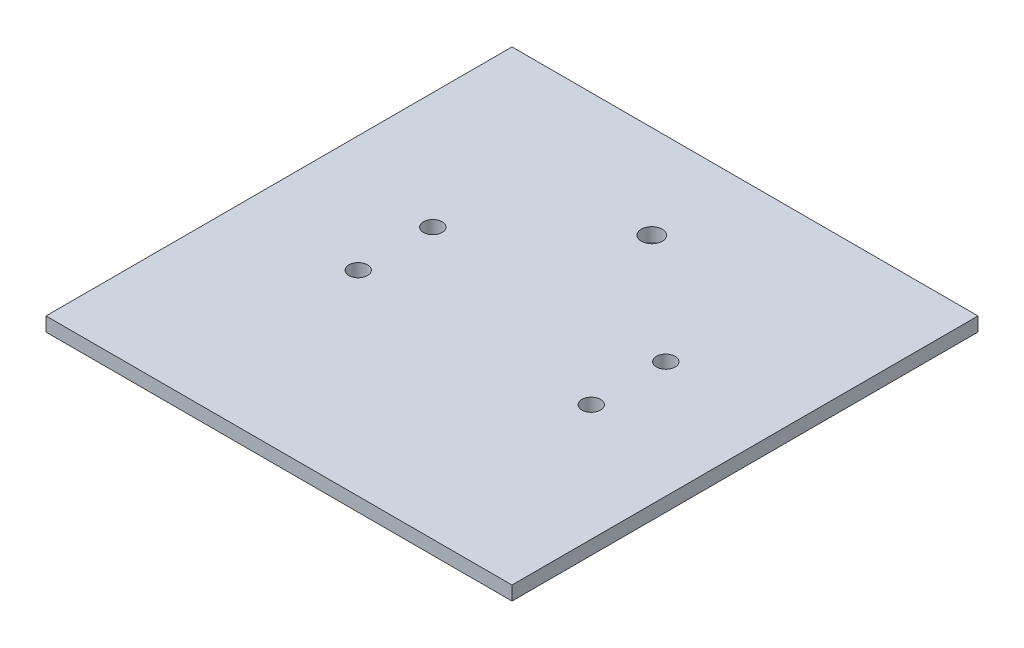
SolidWorks part; units mm, degrees
ref_plane "前视基准面" through (0, 0, 0) normal (0, 0, 1) x (1, 0, 0)
ref_plane "上视基准面" through (0, 0, 0) normal (0, 1, 0) x (1, 0, 0)
ref_plane "右视基准面" through (0, 0, 0) normal (1, 0, 0) x (0, 0, -1)
sketch "草图1" plane through (0, 0, 0) normal (0, 1, 0) x (1, 0, 0)
  line L0 (-100, 100) -> (100, 100)
  line L1 (-100, -100) -> (100, -100)
  line L2 (-100, 100) -> (-100, -100)
  line L3 (100, 100) -> (100, -100)
  circle A0 centre (0, 60) radius 4.5
  circle A1 centre (50, 16) radius 4
  circle A2 centre (50, -16) radius 4
  circle A3 centre (-50, -16) radius 4
  circle A4 centre (-50, 16) radius 4
extrude "凸台-拉伸1" add sketch "草图1" along normal blind 6
